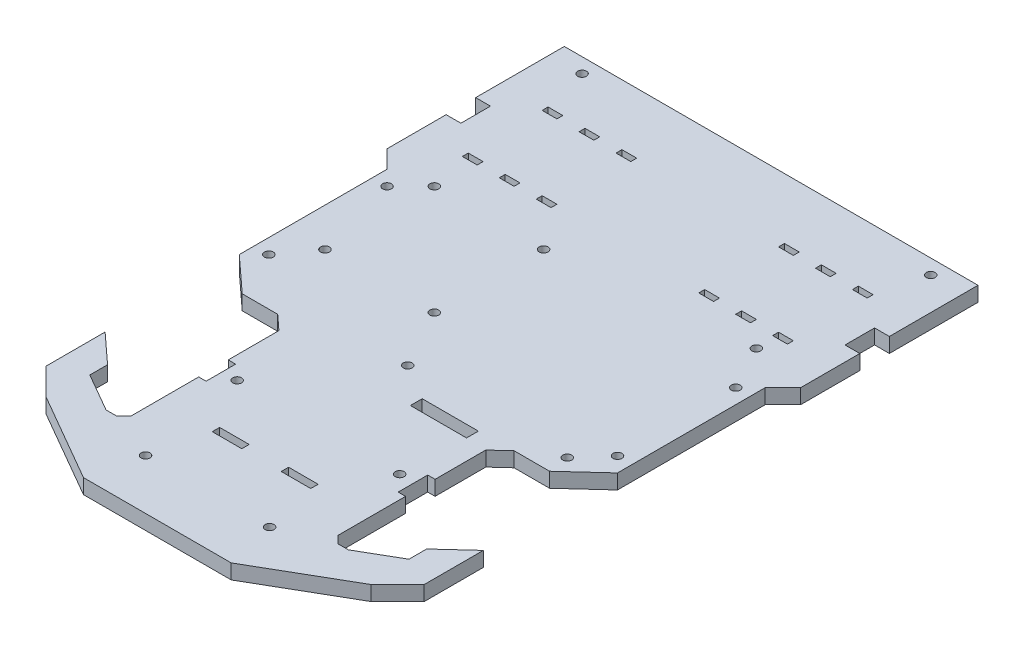
SolidWorks part; units mm, degrees
ref_plane "Front Plane" through (0, 0, 0) normal (0, 0, 1) x (1, 0, 0)
ref_plane "Top Plane" through (0, 0, 0) normal (0, 1, 0) x (1, 0, 0)
ref_plane "Right Plane" through (0, 0, 0) normal (1, 0, 0) x (0, 0, -1)
sketch "Sketch1" plane through (0, 0, 0) normal (0, 1, 0) x (1, 0, 0)
  line L20 (55, -190.4111) -> (64, -181.4111)
  line L21 (64, -181.4111) -> (64, -161.4111)
  line L22 (64, -161.4111) -> (54, -170.5778)
  line L23 (54, -170.5778) -> (54, -176.5778)
  line L24 (54, -176.5778) -> (41, -184.0833)
  line L25 (41, -184.0833) -> (37.5, -184.0833)
  line L26 (37.5, -184.0833) -> (35, -181.5833)
  line L27 (35, -181.5833) -> (35, -131.5833)
  line L28 (35, -131.5833) -> (40, -127)
  line L29 (40, -127) -> (52, -127)
  line L30 (52, -127) -> (64, -116)
  line L31 (64, -116) -> (64, -66)
  line L32 (64, -66) -> (70, -60)
  line L34 (70, -60) -> (70, -40)
  line L35 (70, -40) -> (65, -40)
  line L36 (65, -40) -> (65, -30)
  line L37 (65, -30) -> (70, -30)
  line L38 (70, -30) -> (70, 0)
  line L39 (70, 0) -> (-70, 0)
  line L60 (-25, -207.7316) -> (25, -207.7316)
  line L61 (25, -207.7316) -> (55, -190.4111)
  line L70 (0, 0) -> (0, -207.7316) construction
  line L71 (-25, -207.7316) -> (-55, -190.4111)
  line L72 (-70, -30) -> (-70, 0)
  line L73 (-65, -30) -> (-70, -30)
  line L74 (-65, -40) -> (-65, -30)
  line L75 (-70, -40) -> (-65, -40)
  line L76 (-70, -60) -> (-70, -40)
  line L77 (-64, -66) -> (-70, -60)
  line L78 (-64, -116) -> (-64, -66)
  line L79 (-52, -127) -> (-64, -116)
  line L80 (-40, -127) -> (-52, -127)
  line L81 (-35, -131.5833) -> (-40, -127)
  line L82 (-35, -181.5833) -> (-35, -131.5833)
  line L83 (-37.5, -184.0833) -> (-35, -181.5833)
  line L84 (-41, -184.0833) -> (-37.5, -184.0833)
  line L85 (-54, -176.5778) -> (-41, -184.0833)
  line L86 (-54, -170.5778) -> (-54, -176.5778)
  line L87 (-64, -161.4111) -> (-54, -170.5778)
  line L88 (-64, -181.4111) -> (-64, -161.4111)
  line L89 (-55, -190.4111) -> (-64, -181.4111)
  line L90 (65, -35) -> (0, -35) construction
  line L91 (65, -22.5) -> (15, -22.5) construction
  line L92 (55, -20.5) -> (50, -20.5)
  line L93 (55, -20.5) -> (55, -22.5)
  line L94 (55, -22.5) -> (50, -22.5)
  line L95 (50, -20.5) -> (50, -22.5)
  line L96 (42.5, -20.5) -> (37.5, -20.5)
  line L97 (42.5, -20.5) -> (42.5, -22.5)
  line L98 (42.5, -22.5) -> (37.5, -22.5)
  line L99 (37.5, -20.5) -> (37.5, -22.5)
  line L100 (30, -20.5) -> (25, -20.5)
  line L101 (30, -20.5) -> (30, -22.5)
  line L102 (30, -22.5) -> (25, -22.5)
  line L103 (25, -20.5) -> (25, -22.5)
  line L104 (55, -47.5) -> (50, -47.5)
  line L105 (50, -49.5) -> (50, -47.5)
  line L106 (55, -49.5) -> (50, -49.5)
  line L107 (55, -49.5) -> (55, -47.5)
  line L108 (42.5, -47.5) -> (37.5, -47.5)
  line L109 (37.5, -49.5) -> (37.5, -47.5)
  line L110 (42.5, -49.5) -> (37.5, -49.5)
  line L111 (42.5, -49.5) -> (42.5, -47.5)
  line L112 (30, -47.5) -> (25, -47.5)
  line L113 (25, -49.5) -> (25, -47.5)
  line L114 (30, -49.5) -> (25, -49.5)
  line L115 (30, -49.5) -> (30, -47.5)
  line L116 (-55, -49.5) -> (-55, -47.5)
  line L117 (-55, -49.5) -> (-50, -49.5)
  line L118 (-50, -49.5) -> (-50, -47.5)
  line L119 (-55, -47.5) -> (-50, -47.5)
  line L120 (-42.5, -49.5) -> (-42.5, -47.5)
  line L121 (-42.5, -49.5) -> (-37.5, -49.5)
  line L122 (-37.5, -49.5) -> (-37.5, -47.5)
  line L123 (-42.5, -47.5) -> (-37.5, -47.5)
  line L124 (-30, -49.5) -> (-30, -47.5)
  line L125 (-30, -49.5) -> (-25, -49.5)
  line L126 (-25, -49.5) -> (-25, -47.5)
  line L127 (-30, -47.5) -> (-25, -47.5)
  line L128 (-55, -22.5) -> (-50, -22.5)
  line L129 (-50, -20.5) -> (-50, -22.5)
  line L130 (-55, -20.5) -> (-50, -20.5)
  line L131 (-55, -20.5) -> (-55, -22.5)
  line L132 (-42.5, -22.5) -> (-37.5, -22.5)
  line L133 (-37.5, -20.5) -> (-37.5, -22.5)
  line L134 (-42.5, -20.5) -> (-37.5, -20.5)
  line L135 (-42.5, -20.5) -> (-42.5, -22.5)
  line L136 (-30, -22.5) -> (-25, -22.5)
  line L137 (-25, -20.5) -> (-25, -22.5)
  line L138 (-30, -20.5) -> (-25, -20.5)
  line L139 (-30, -20.5) -> (-30, -22.5)
  circle A0 centre (59, -5) radius 1.5
  circle A1 centre (59, -71) radius 1.5
  circle A2 centre (59, -111) radius 1.5
  circle A3 centre (-59, -111) radius 1.5
  circle A4 centre (-59, -71) radius 1.5
  circle A5 centre (-59, -5) radius 1.5
  point P56 (52.5, -22.5)
  point P62 (40, -22.5)
  point P63 (27.5, -22.5)
  point P64 (27.5, -22.5)
  point P65 (40, -22.5)
  point P66 (52.5, -22.5)
  point P106 (0, -127)
  dimension "D30" = 3
  dimension "D1" = 70
  dimension "D2" = 30
  dimension "D4" = 5
  dimension "D5" = 20
  dimension "D6" = 6
  dimension "D7" = 135
  dimension "D8" = 10
  dimension "D9" = 11
  dimension "D10" = 12
  dimension "D11" = 5
  dimension "D12" = 50
  dimension "D13" = 2.5
  dimension "D14" = 135
  dimension "D15" = 3.5
  dimension "D16" = 30
  dimension "D18" = 6
  dimension "D19" = 10
  dimension "D20" = 20
  dimension "D21" = 9
  dimension "D22" = 30
  dimension "D23" = 135
  dimension "D24" = 150
  dimension "D25" = 50
  dimension "D26" = 5
  dimension "D27" = 2
  dimension "D28" = 12.5
  dimension "D29" = 50
  dimension "D31" = 5
  dimension "D33" = 5
  dimension "D34" = 5
  dimension "D32" = 5
  dimension "D37" = 35
extrude "Boss-Extrude1" add sketch "Sketch1" along normal blind 5
sketch "Sensor Pos" plane through (0, 0, 0) normal (0, -1, 0) x (1, 0, 0)
  line L1 (32, 167.7316) -> (-32, 167.7316)
  line L2 (32, 167.7316) -> (32, 139.7316)
  line L3 (32, 139.7316) -> (-32, 139.7316)
  line L4 (-32, 167.7316) -> (-32, 139.7316)
  line L5 (-25, 207.7316) -> (25, 207.7316) construction
  line L6 (24.5, 190.7316) -> (-24.5, 190.7316) construction
  line L7 (24.5, 206.7316) -> (-24.5, 206.7316)
  line L8 (24.5, 206.7316) -> (24.5, 174.7316)
  line L9 (24.5, 174.7316) -> (-24.5, 174.7316)
  line L10 (-24.5, 206.7316) -> (-24.5, 174.7316)
  line L11 (35, 181.5833) -> (35, 131.5833) construction
  line L12 (35, 158.7316) -> (32.5, 158.7316)
  line L13 (35, 158.7316) -> (35, 148.7316)
  line L14 (35, 148.7316) -> (32.5, 148.7316)
  line L15 (32.5, 158.7316) -> (32.5, 148.7316)
  line L16 (0, 167.7316) -> (0, 139.7316) construction
  line L17 (-35, 148.7316) -> (-32.5, 148.7316)
  line L18 (-32.5, 158.7316) -> (-32.5, 148.7316)
  line L19 (-35, 158.7316) -> (-32.5, 158.7316)
  line L20 (-35, 158.7316) -> (-35, 148.7316)
  line L21 (35, 131.5833) -> (40, 127) construction
  line L22 (28.2, 131.2917) -> (9.2, 131.2917)
  line L23 (28.2, 131.2917) -> (28.2, 127.2917)
  line L24 (28.2, 127.2917) -> (9.2, 127.2917)
  line L25 (9.2, 131.2917) -> (9.2, 127.2917)
  line L26 (28.2, 131.2917) -> (9.2, 127.2917) construction
  line L27 (28.2, 127.2917) -> (9.2, 131.2917) construction
  line L28 (35, 174.7316) -> (35, 167.7316) construction
  line L29 (35, 171.2316) -> (-35, 171.2316) construction
  line L30 (-35, 131.5833) -> (-35, 181.5833) construction
  line L32 (-6.6667, 172.4816) -> (-16.6667, 172.4816)
  line L33 (-6.6667, 172.4816) -> (-6.6667, 169.9816)
  line L34 (-6.6667, 169.9816) -> (-16.6667, 169.9816)
  line L35 (-16.6667, 172.4816) -> (-16.6667, 169.9816)
  line L36 (-6.6667, 172.4816) -> (-16.6667, 169.9816) construction
  line L37 (-6.6667, 169.9816) -> (-16.6667, 172.4816) construction
  line L38 (16.6667, 172.4816) -> (6.6667, 172.4816)
  line L39 (16.6667, 172.4816) -> (16.6667, 169.9816)
  line L40 (16.6667, 169.9816) -> (6.6667, 169.9816)
  line L41 (6.6667, 172.4816) -> (6.6667, 169.9816)
  line L42 (16.6667, 172.4816) -> (6.6667, 169.9816) construction
  line L43 (16.6667, 169.9816) -> (6.6667, 172.4816) construction
  circle A4 centre (-21, 190.7316) radius 1.5
  circle A5 centre (21, 190.7316) radius 1.5
  circle A6 centre (27.5, 153.2316) radius 1.5
  circle A7 centre (-27.5, 153.2316) radius 1.5
  point P6 (0, 207.7316)
  point P7 (0, 167.7316)
  point P20 (0, 206.7316)
  point P33 (32, 153.7316)
  point P34 (32.5, 153.7316)
  point P41 (18.7, 129.2917)
  point P51 (37.5, 129.2917)
  point P56 (-11.6667, 171.2316)
  point P61 (11.6667, 171.2316)
  point P66 (11.6667, 171.2316)
  point P67 (-11.6667, 171.2316)
  dimension "D14" = 3
  dimension "D5" = 3
  dimension "D1" = 64
  dimension "D2" = 28
  dimension "D10" = 40
  dimension "D11" = 49
  dimension "D12" = 32
  dimension "D13" = 1
  dimension "D15" = 3.5
  dimension "D16" = 3.5
  dimension "D17" = 2.5
  dimension "D18" = 10
  dimension "D19" = 19
  dimension "D20" = 4
  dimension "D21" = 2.5
  dimension "D22" = 10
  dimension "D3" = 27.5
  dimension "D4" = 27.5
  dimension "D6" = 13.5
  dimension "D7" = 6.8
extrude "Cut-Extrude1" cut sketch "Sensor Pos" against normal through all contours A6 | A7 | A4 | A5 | L17 L18 L19 L20 | L13 L12 L15 L14 | L23 L22 L25 L24 | L33 L32 L35 L34 | L39 L38 L41 L40
sketch "Sketch2" plane through (0, 5, 0) normal (0, 1, 0) x (1, 0, 0)
  line L0 (-64, -66) -> (-64, -116) construction
  line L1 (-11, -60) -> (-54, -60)
  line L2 (-11, -60) -> (-11, -103)
  line L3 (-11, -103) -> (-54, -103)
  line L4 (-54, -60) -> (-54, -103)
  line L5 (64, -116) -> (64, -66) construction
  line L6 (54, -53) -> (-6, -53)
  line L7 (54, -53) -> (54, -123)
  line L8 (54, -123) -> (-6, -123)
  line L9 (-6, -53) -> (-6, -123)
  line L10 (40, -127) -> (52, -127) construction
  circle A0 centre (-51, -63) radius 1.5
  circle A1 centre (-51, -100) radius 1.5
  circle A2 centre (-14, -100) radius 1.5
  circle A3 centre (-14, -63) radius 1.5
  circle A5 centre (-3, -120) radius 1.5
  circle A6 centre (51, -120) radius 1.5
  circle A7 centre (51, -56) radius 1.5
  dimension "D14" = 3
  dimension "D5" = 3
  dimension "D3" = 3
  dimension "D12" = 3
  dimension "D1" = 43
  dimension "D2" = 10
  dimension "D4" = 3
  dimension "D6" = 3
  dimension "D7" = 3
  dimension "D8" = 60
  dimension "D9" = 70
  dimension "D10" = 10
  dimension "D11" = 4
  dimension "D13" = 3
  dimension "D15" = 3
  dimension "D16" = 3
extrude "Cut-Extrude2" cut sketch "Sketch2" against normal through all and the other way through all contours A0 | A3 | A1 | A2 | A7 | A5 | A6
sketch "Sketch3" plane through (0, 5, 0) normal (0, 1, 0) x (1, 0, 0)
  line L0 (120.3931, -117.4352) -> (157.4008, -117.4352) construction
equation "\"D16@Sensor Pos\"=\"D15@Sensor Pos\""
equation "\"thick5mm\" = 5mm"
equation "\"D4@Sketch1\" = \"thick5mm\""
equation "\"D17@Sensor Pos\"=\"thick2.5mm\""
equation "\"thick2.5mm\"=0.25"
equation "\"D21@Sensor Pos\"=\"thick2.5mm\""
equation "\"l298\"=4.3"
equation "\"D1@Sketch2\"=\"l298\""
equation "\"drill\"=0.3"
equation "\"D3@Sketch2\"=\"drill\""
equation "\"D30@Sketch1\"=\"drill\""
equation "\"D14@Sensor Pos\"=\"drill\""
equation "\"D12@Sketch2\"=\"drill\""
equation "\"D1@Boss-Extrude1\"=\"thick5mm\""
equation "\"D3@Sensor Pos\"=5.5/2"
equation "\"D4@Sensor Pos\"=\"D3@Sensor Pos\""
equation "\"D5@Sensor Pos\"=\"drill\""
